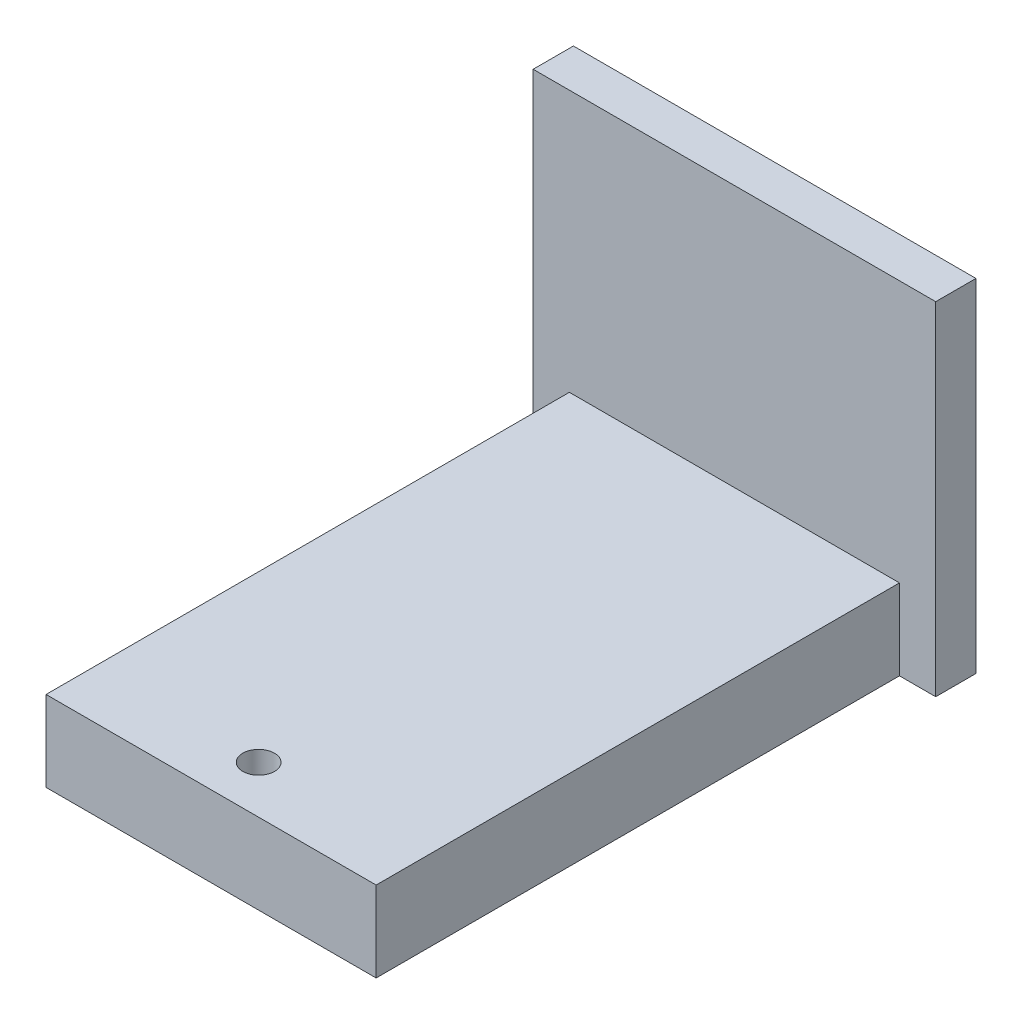
SolidWorks part; units mm, degrees
ref_plane "Front Plane" through (0, 0, 0) normal (0, 0, 1) x (1, 0, 0)
ref_plane "Top Plane" through (0, 0, 0) normal (0, 1, 0) x (1, 0, 0)
ref_plane "Right Plane" through (0, 0, 0) normal (1, 0, 0) x (0, 0, -1)
sketch "Sketch1" plane through (0, 0, 0) normal (0, 0, 1) x (1, 0, 0)
  line L1 (0, 0) -> (25.4, 0)
  line L2 (0, 0) -> (0, -25.4)
  line L3 (0, -25.4) -> (25.4, -25.4)
  line L4 (25.4, 0) -> (25.4, -25.4)
  dimension "D1" = 25.4
  dimension "D2" = 25.4
extrude "Boss-Extrude1" add sketch "Sketch1" along normal blind 2.54
ref_plane "Plane1" through (0, -19.05, 0) normal (0, 1, 0) x (1, 0, 0)
sketch "Sketch2" plane through (0, -19.05, 0) normal (0, 1, 0) x (1, 0, 0)
  line L0 (25.4, -2.54) -> (0, -2.54) construction
  line L1 (2.286, -35.56) -> (2.286, -2.54)
  line L2 (2.286, -2.54) -> (12.7, -2.54)
  line L3 (12.7, -2.54) -> (23.114, -2.54)
  line L4 (23.114, -2.54) -> (23.114, -35.56)
  line L5 (2.286, -35.56) -> (23.114, -35.56)
  point P13 (12.7, -2.54)
  dimension "D2" = 33.02
extrude "Boss-Extrude3" add sketch "Sketch2" along normal mid plane 5.08 contours L5 L2 L1 | L5 L4 L3
sketch "Sketch3" plane through (0, -16.51, 0) normal (0, 1, 0) x (1, 0, 0)
  line L0 (2.286, -35.56) -> (4.826, -35.56)
  line L1 (20.574, -35.56) -> (23.114, -35.56)
  arc A0 (2.286, -35.56) -> (23.114, -35.56) centre (12.7, -35.56) cw
  arc A1 (4.826, -35.56) -> (20.574, -35.56) centre (12.7, -35.56) cw
  dimension "D1" = 2.54
extrude "Boss-Extrude4" [suppressed] add sketch "Sketch3" against normal blind 0.635
mirror "Mirror1" [suppressed] about plane through (0, -19.05, 0) normal (0, 1, 0)
sketch "Sketch4" [suppressed] plane through (2.286, 0, 0) normal (-1, 0, 0) x (0, 0, 1)
  line L1 (2.54, -16.51) -> (35.56, -16.51)
  line L2 (2.54, -16.51) -> (2.54, -21.59)
  line L3 (2.54, -21.59) -> (35.56, -21.59)
  line L4 (35.56, -16.51) -> (35.56, -21.59)
extrude "Boss-Extrude5" [suppressed] add sketch "Sketch4" along normal up to surface (2.286 mm away)
sketch "Sketch5" [suppressed] plane through (23.114, 0, 0) normal (1, 0, 0) x (0, 0, -1)
  line L1 (-35.56, -16.51) -> (-2.54, -16.51)
  line L2 (-35.56, -16.51) -> (-35.56, -21.59)
  line L3 (-35.56, -21.59) -> (-2.54, -21.59)
  line L4 (-2.54, -16.51) -> (-2.54, -21.59)
extrude "Boss-Extrude6" [suppressed] add sketch "Sketch5" along normal up to surface (2.286 mm away)
sketch "Sketch6" plane through (0, 0, 35.56) normal (0, 0, 1) x (1, 0, 0)
  line L0 (25.4, -25.4) -> (25.4, 0) construction
  line L1 (0, -25.4) -> (25.4, -25.4)
  line L2 (0, -25.4) -> (0, -21.59)
  line L3 (0, -21.59) -> (25.4, -21.59)
  line L4 (25.4, -25.4) -> (25.4, -21.59)
  line L5 (2.286, -21.59) -> (23.114, -21.59) construction
extrude "Cut-Extrude1" cut sketch "Sketch6" against normal through all
sketch "Sketch7" plane through (0, -21.59, 0) normal (0, -1, 0) x (-1, 0, 0)
  line L0 (-23.114, -2.54) -> (-23.114, -35.56) construction
  line L1 (-2.286, -35.56) -> (-23.114, -35.56) construction
  circle A0 centre (-12.7, -32.56) radius 1
  point P4 (0, 0)
  dimension "D2" = 2
  dimension "D1" = 10.414
  dimension "D3" = 3
extrude "Cut-Extrude2" cut sketch "Sketch7" against normal through all
